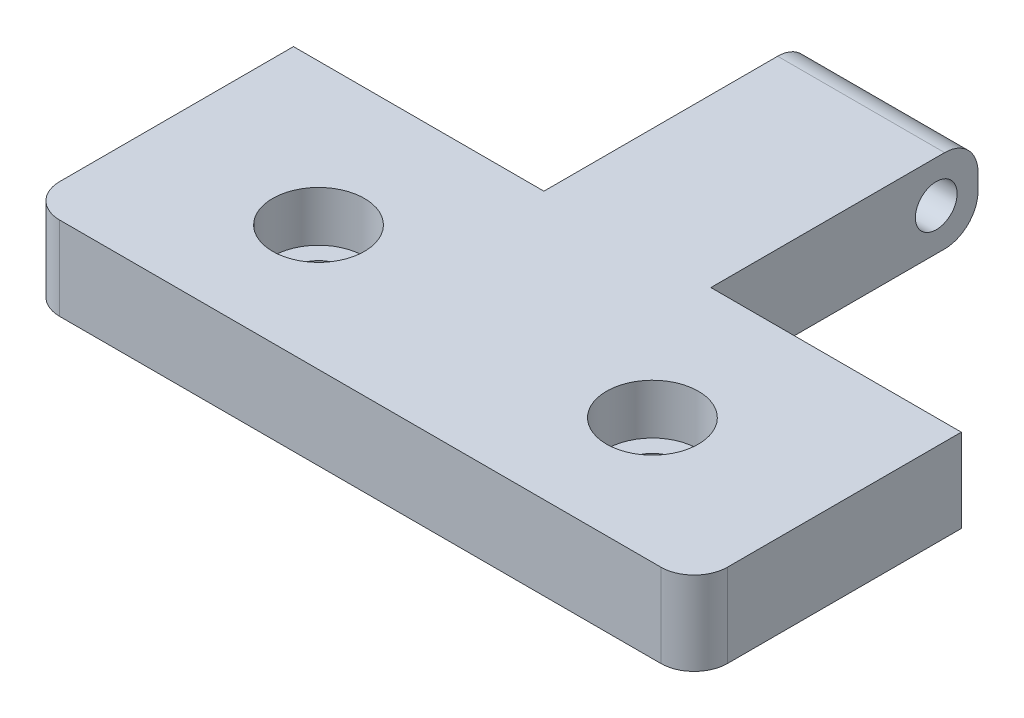
SolidWorks part; units mm, degrees
ref_plane "정면" through (0, 0, 0) normal (0, 0, 1) x (1, 0, 0)
ref_plane "윗면" through (0, 0, 0) normal (0, 1, 0) x (1, 0, 0)
ref_plane "우측면" through (0, 0, 0) normal (1, 0, 0) x (0, 0, -1)
sketch "스케치1" plane through (0, 0, 0) normal (0, 1, 0) x (1, 0, 0)
  line L0 (50, 32) -> (80, 32)
  line L1 (0, 0) -> (80, 0)
  line L2 (0, 0) -> (0, 32)
  line L3 (0, 32) -> (30, 32)
  line L4 (80, 0) -> (80, 32)
  line L6 (30, 32) -> (30, 64)
  line L7 (30, 64) -> (50, 64)
  line L8 (50, 32) -> (50, 64)
  dimension "D1" = 80
  dimension "D2" = 20
  dimension "D3" = 30
  dimension "D4" = 32
  dimension "D5" = 32
extrude "보스-돌출1" add sketch "스케치1" along normal blind 10
fillet "필렛1" radius 4 2 edges at (40, 0, -64) (40, 10, -64)
sketch "스케치2" plane through (50, 0, 0) normal (1, 0, 0) x (0, 0, -1)
  line L0 (32, 10) -> (60, 10) construction
  line L3 (64, 6) -> (64, 4) construction
  circle A0 centre (59, 5) radius 2.5
  dimension "D2" = 5
  dimension "D1" = 5
  dimension "D3" = 5
extrude "컷-돌출1" cut sketch "스케치2" against normal through all
fillet "필렛2" radius 4 2 edges at (0, 5, 0) (80, 5, 0)
sketch "스케치3" plane through (0, 10, 0) normal (0, 1, 0) x (1, 0, 0)
  line L0 (4, 0) -> (76, 0) construction
  line L1 (0, 32) -> (0, 4) construction
  circle A0 centre (20, 15) radius 5.5
  circle A1 centre (60, 15) radius 5.5
  dimension "D4" = 11
  dimension "D1" = 15
  dimension "D2" = 20
  dimension "D3" = 40
extrude "컷-돌출2" cut sketch "스케치3" against normal blind 6
sketch "스케치4" plane through (0, 4, 0) normal (0, 1, 0) x (1, 0, 0)
  circle A0 centre (20, 15) radius 3.25
  circle A1 centre (60, 15) radius 3.25
  dimension "D1" = 6.5
  dimension "D2" = 6.5
extrude "컷-돌출3" cut sketch "스케치4" against normal through all
